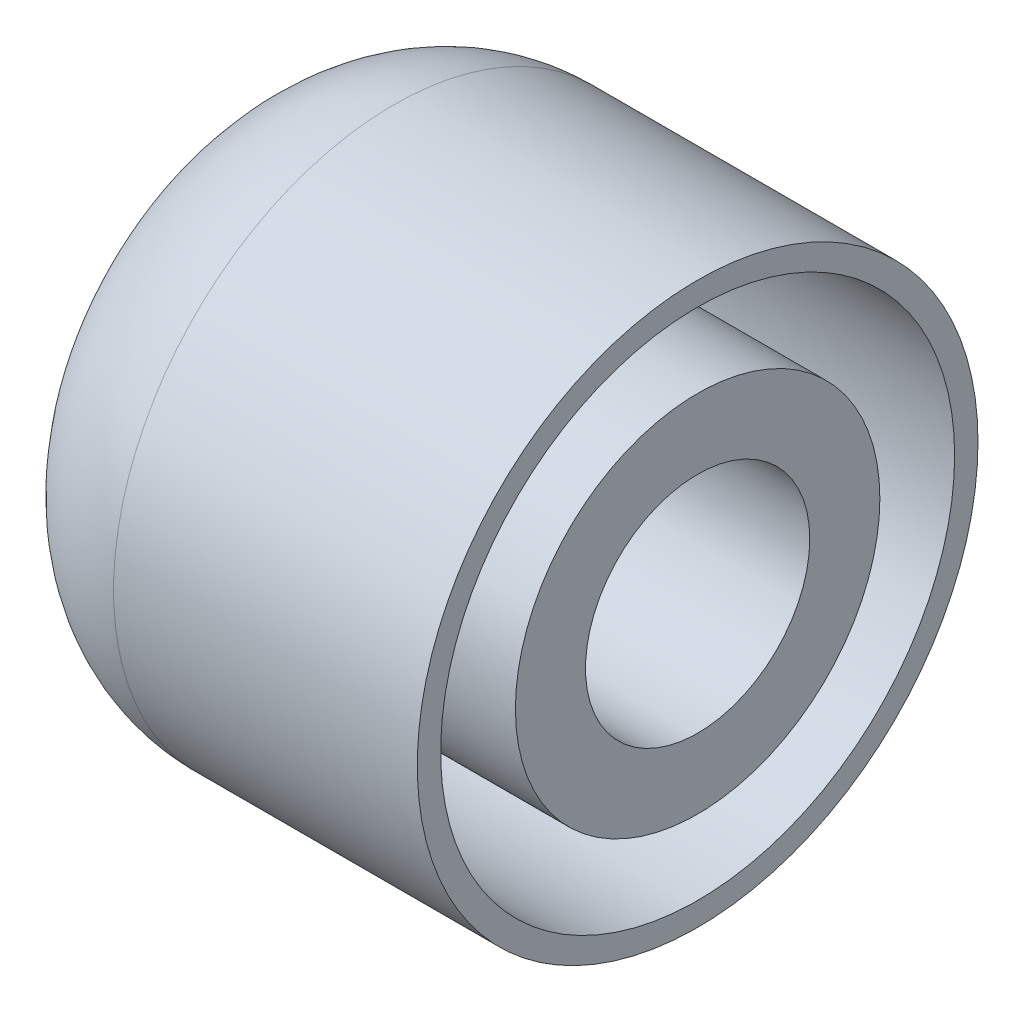
SolidWorks part; units mm, degrees
ref_plane "Front Plane" through (0, 0, 0) normal (0, 0, 1) x (1, 0, 0)
ref_plane "Top Plane" through (0, 0, 0) normal (0, 1, 0) x (1, 0, 0)
ref_plane "Right Plane" through (0, 0, 0) normal (1, 0, 0) x (0, 0, -1)
sketch "Sketch1" plane through (0, 0, 0) normal (0, 0, 1) x (1, 0, 0)
  line L0 (0, 6) -> (-6.5, 6)
  line L1 (-10, 2.5) -> (-10, 2.4)
  line L2 (-10, 2.4) -> (0, 2.4)
  line L3 (0, 2.4) -> (0, 3.9)
  line L4 (0, 3.9) -> (-6, 3.9)
  line L5 (-6, 3.9) -> (-6, 5.5)
  line L6 (-6, 5.5) -> (0, 5.5)
  line L7 (0, 5.5) -> (0, 6)
  line L8 (0, 0) -> (-10, 0) construction
  arc A0 (-6.5, 6) -> (-10, 2.5) centre (-6.5, 2.5) ccw
  dimension "D8" = 3.5
  dimension "D1" = 10
  dimension "D2" = 4.8
  dimension "D3" = 7.8
  dimension "D4" = 11
  dimension "D5" = 12
  dimension "D6" = 6
  dimension "D7" = 10
revolve "Ear insert" add sketch "Sketch1" angle 360 about L8
